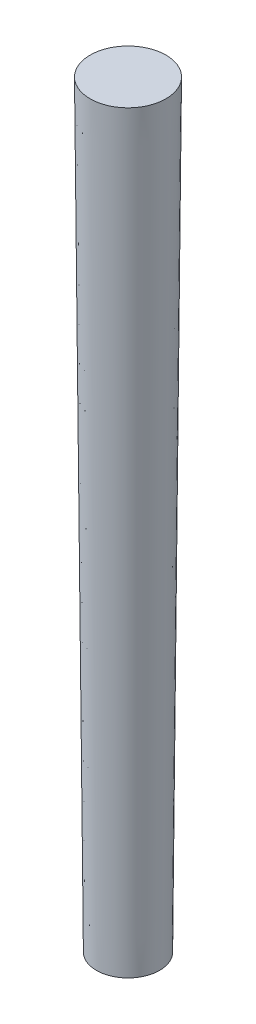
SolidWorks part; units mm, degrees
ref_plane "Front" through (0, 0, 0) normal (0, 0, 1) x (1, 0, 0)
ref_plane "Top" through (0, 0, 0) normal (0, 1, 0) x (1, 0, 0)
ref_plane "Right" through (0, 0, 0) normal (1, 0, 0) x (0, 0, -1)
sketch "Sketch1" plane through (0, 0, 0) normal (0, 0, 1) x (1, 0, 0)
  line L0 (0, -30) -> (0, 30)
  line L1 (0, 30) -> (3, 30)
  line L2 (3, 30) -> (2.5, -30)
  line L3 (2.5, -30) -> (0, -30)
  point P4 (0, 0)
  dimension "D1" = 60
  dimension "D2" = 3
  dimension "D3" = 2.5
revolve "Revolve1" add sketch "Sketch1" angle 360 about L0
scale "Scale1" scale about centroid uniform scaling yes scale factor 0.33
